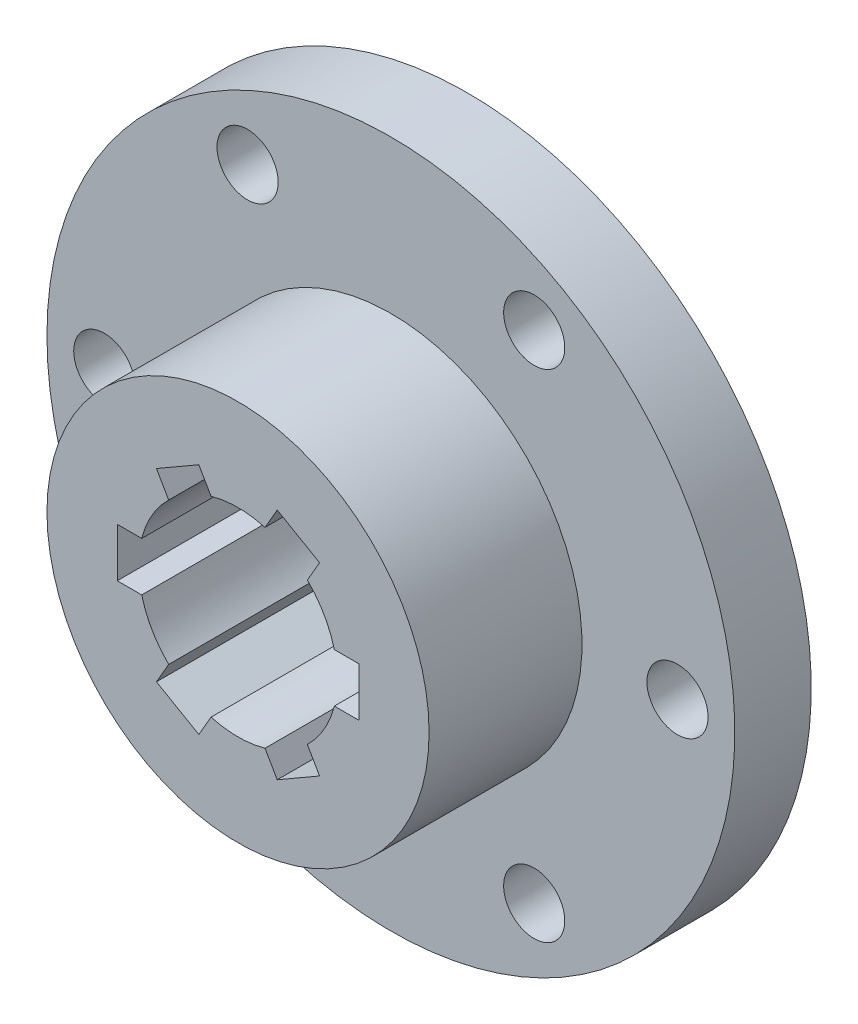
SolidWorks part; units mm, degrees
ref_plane "Front Plane" through (0, 0, 0) normal (0, 0, 1) x (1, 0, 0)
ref_plane "Top Plane" through (0, 0, 0) normal (0, 1, 0) x (1, 0, 0)
ref_plane "Right Plane" through (0, 0, 0) normal (1, 0, 0) x (0, 0, -1)
sketch "Sketch1" plane through (0, 0, 0) normal (0, 0, 1) x (1, 0, 0)
  circle A0 centre (0, 0) radius 15.875
  dimension "D1" = 31.75
extrude "Boss-Extrude1" add sketch "Sketch1" along normal blind 12.7
sketch "Sketch4" plane through (0, 0, 0) normal (0, 0, -1) x (-1, 0, 0)
  circle A0 centre (0, 0) radius 28.575
  dimension "D1" = 57.15
extrude "Boss-Extrude3" add sketch "Sketch4" along normal blind 6.35
sketch "Sketch5" plane through (0, 0, 12.7) normal (0, 0, 1) x (1, 0, 0)
  line L0 (6.7763, -7.6728) -> (5.7603, -5.9131)
  line L1 (10.033, 2.032) -> (8.001, 2.032)
  line L2 (10.033, 2.032) -> (10.033, -2.032)
  line L3 (10.033, -2.032) -> (8.001, -2.032)
  line L4 (6.7763, -7.6728) -> (3.2567, -9.7048)
  line L5 (3.2567, -9.7048) -> (2.2407, -7.9451)
  line L7 (-3.2567, -9.7048) -> (-2.2407, -7.9451)
  line L8 (-3.2567, -9.7048) -> (-6.7763, -7.6728)
  line L9 (-6.7763, -7.6728) -> (-5.7603, -5.9131)
  line L10 (-10.033, -2.032) -> (-8.001, -2.032)
  line L11 (-10.033, -2.032) -> (-10.033, 2.032)
  line L12 (-10.033, 2.032) -> (-8.001, 2.032)
  line L13 (-6.7763, 7.6728) -> (-5.7603, 5.9131)
  line L14 (-6.7763, 7.6728) -> (-3.2567, 9.7048)
  line L15 (-3.2567, 9.7048) -> (-2.2407, 7.9451)
  line L16 (3.2567, 9.7048) -> (2.2407, 7.9451)
  line L17 (3.2567, 9.7048) -> (6.7763, 7.6728)
  line L18 (6.7763, 7.6728) -> (5.7603, 5.9131)
  arc A0 (8.001, 2.032) -> (5.7603, 5.9131) centre (0, 0) ccw
  arc A1 (2.2407, 7.9451) -> (-2.2407, 7.9451) centre (0, 0) ccw
  arc A2 (5.7603, -5.9131) -> (8.001, -2.032) centre (0, 0) ccw
  arc A3 (-2.2407, -7.9451) -> (2.2407, -7.9451) centre (0, 0) ccw
  arc A4 (-8.001, -2.032) -> (-5.7603, -5.9131) centre (0, 0) ccw
  arc A5 (-5.7603, 5.9131) -> (-8.001, 2.032) centre (0, 0) ccw
  point P3 (8.255, 0)
  point P32 (0, 0)
  dimension "D1" = 16.51
  dimension "D2" = 4.064
  dimension "D3" = 2.032
  dimension "D4" = 6
extrude "Cut-Extrude2" cut sketch "Sketch5" against normal up to surface (19.05 mm away) up to face at (-28.575, 0, -6.35)
sketch "Sketch6" plane through (0, 0, -6.35) normal (0, 0, -1) x (-1, 0, 0)
  circle A1 centre (-23.8125, 0) radius 2.54
  circle A2 centre (-11.9062, 20.6222) radius 2.54
  circle A3 centre (11.9063, 20.6222) radius 2.54
  circle A4 centre (23.8125, 0) radius 2.54
  circle A5 centre (11.9062, -20.6222) radius 2.54
  circle A6 centre (-11.9063, -20.6222) radius 2.54
  point P17 (0, 0)
  dimension "D2" = 5.08
  dimension "D3" = 6
extrude "Cut-Extrude3" cut sketch "Sketch6" against normal up to surface (6.35 mm away) up to face at (-28.575, 0, 0)
